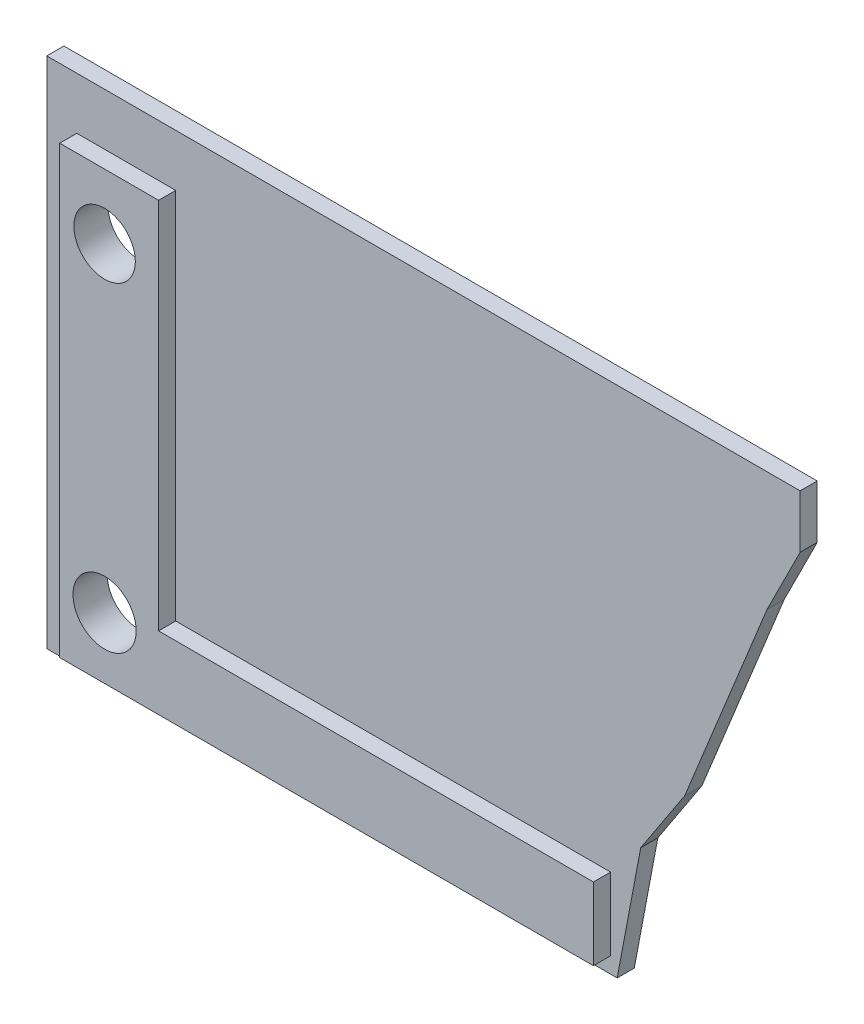
SolidWorks part; units mm, degrees
ref_plane "Alzado" through (0, 0, 0) normal (0, 0, 1) x (1, 0, 0)
ref_plane "Planta" through (0, 0, 0) normal (0, 1, 0) x (1, 0, 0)
ref_plane "Vista lateral" through (0, 0, 0) normal (1, 0, 0) x (0, 0, -1)
sketch "Croquis1" plane through (0, 0, 0) normal (0, 0, 1) x (1, 0, 0)
  line L0 (-55.6864, 130.5711) -> (-55.6864, -49.4289)
  line L1 (-55.6864, -49.4289) -> (144.3136, -49.4289)
  line L2 (-55.6864, 130.5711) -> (182.3568, 130.5711)
  line L3 (182.3568, 130.5711) -> (208.451, 130.5711)
  line L4 (208.451, 130.5711) -> (208.451, 111.9095)
  line L5 (144.3136, -49.4289) -> (152.5628, -5.7501)
  line L6 (152.5628, -5.7501) -> (168.0056, 17.7818)
  line L7 (168.0056, 17.7818) -> (182.3568, 53.0797)
  line L8 (182.3568, 53.0797) -> (196.8655, 88.7648)
  line L9 (196.8655, 88.7648) -> (208.451, 111.9095)
  line L10 (208.451, 111.9095) -> (209.9218, 110.4387)
extrude "Saliente-Extruir1" add sketch "Croquis1" along normal blind 6 contours L8 L9 L4 L3 L2 L0 L1 L5 L6 L7
sketch "Croquis2" plane through (0, 0, 6) normal (0, 0, 1) x (1, 0, 0)
  line L1 (-45.1468, 112.333) -> (-10.4775, 112.333)
  line L2 (-45.1468, 112.333) -> (-45.1468, -43.8655)
  line L3 (-45.1468, -43.8655) -> (-10.4775, -43.8655)
  line L4 (-10.4775, 112.333) -> (-10.4775, -43.8655)
  line L5 (142.3659, -28.8655) -> (-10.4775, -28.8655)
  line L6 (142.3659, -28.8655) -> (142.3659, -43.8655)
  line L7 (142.3659, -43.8655) -> (-10.4775, -43.8655)
  line L8 (-10.4775, -28.8655) -> (-10.4775, -43.8655)
extrude "Saliente-Extruir2" add sketch "Croquis2" along normal blind 6 contours L4 L1 L2 L3
sketch "Croquis4" plane through (0, 0, 6) normal (0, 0, 1) x (1, 0, 0)
  line L0 (-10.4775, 112.333) -> (-10.4775, -43.8655) construction
  line L1 (-10.4775, -18.4296) -> (141.9833, -18.4296)
  line L2 (-10.4775, -18.4296) -> (-10.4775, -43.8655)
  line L3 (-10.4775, -43.8655) -> (141.9833, -43.8655)
  line L4 (141.9833, -18.4296) -> (141.9833, -43.8655)
extrude "Saliente-Extruir3" add sketch "Croquis4" along normal blind 6
sketch "Croquis5" plane through (0, 0, 12) normal (0, 0, 1) x (1, 0, 0)
  circle A0 centre (-29.4117, -22.3646) radius 11.0765
  circle A1 centre (-29.4117, 89.6578) radius 10.7752
extrude "Cortar-Extruir1" cut sketch "Croquis5" against normal blind 12
